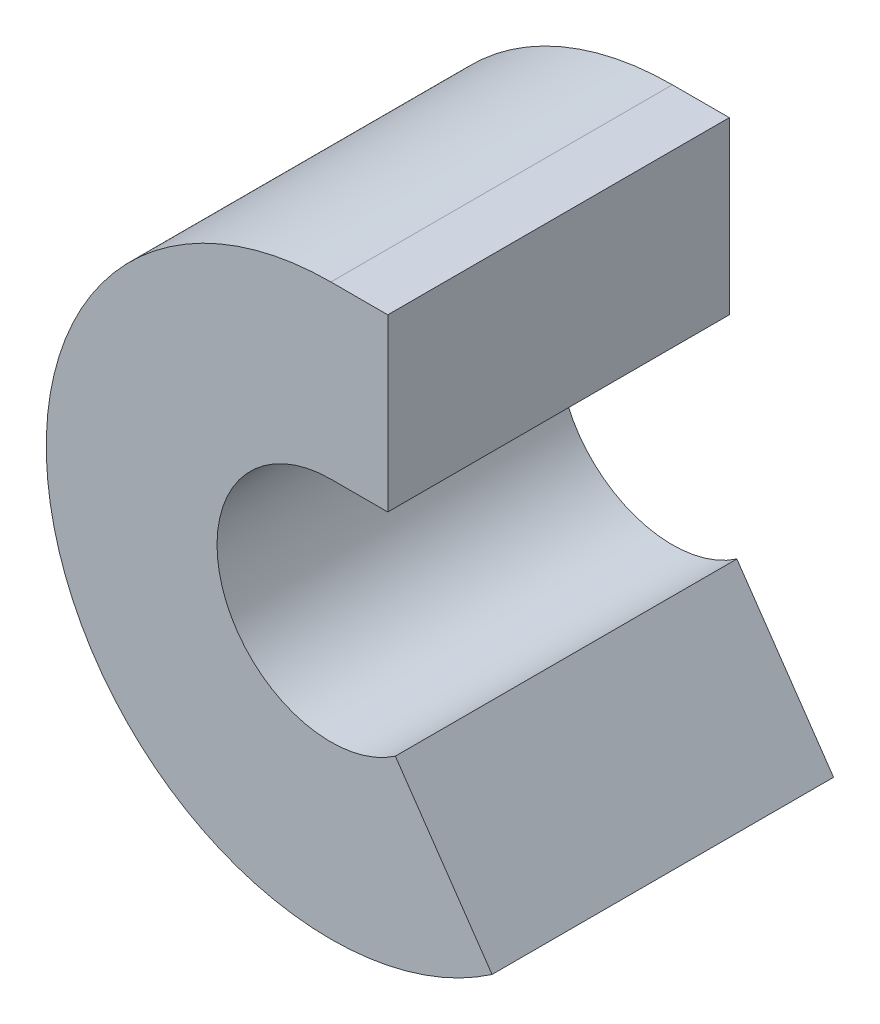
SolidWorks part; units mm, degrees
ref_plane "Front Plane" through (0, 0, 0) normal (0, 0, 1) x (1, 0, 0)
ref_plane "Top Plane" through (0, 0, 0) normal (0, 1, 0) x (1, 0, 0)
ref_plane "Right Plane" through (0, 0, 0) normal (1, 0, 0) x (0, 0, -1)
sketch "Sketch1" plane through (0, 0, 0) normal (0, 0, 1) x (1, 0, 0)
  line L0 (-263.2582, 0) -> (-136.1282, 0) construction
  line L1 (-263.2582, 25.4) -> (-250.5582, 25.4)
  line L3 (-263.2582, 0) -> (-136.1282, 0) construction
  line L4 (-263.2582, 63.5) -> (-250.5582, 63.5)
  line L5 (-248.799, -20.8828) -> (-248.871, -20.9325)
  line L6 (-250.5582, 63.5) -> (-250.5582, 25.4)
  line L7 (-248.871, -20.9325) -> (-227.2902, -52.3311)
  arc A0 (-263.2582, 25.4) -> (-263.2582, -25.4) centre (-263.2582, 0) ccw
  arc A2 (-263.2582, 63.5) -> (-263.2582, -63.5) centre (-263.2582, 0) ccw
  arc A4 (-263.2582, 25.4) -> (-248.799, -20.8828) centre (-263.2582, 0) ccw
  arc A5 (-263.2176, 63.5) -> (-227.2902, -52.3311) centre (-263.2582, 0) ccw
  point P3 (-199.6282, 0)
  point P8 (-199.6282, 0)
  dimension "D3" = 25.4
  dimension "D1" = 38.1
  dimension "D2" = 12.7
extrude "Boss-Extrude1" add sketch "Sketch1" along normal blind 76.2
